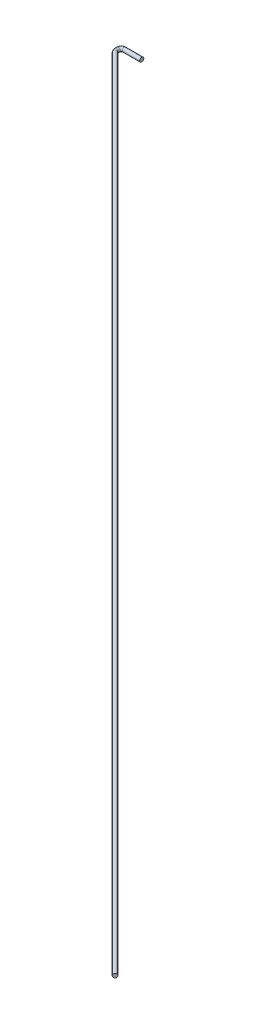
SolidWorks part; units mm, degrees
ref_plane "Front Plane" through (0, 0, 0) normal (0, 0, 1) x (1, 0, 0)
ref_plane "Top Plane" through (0, 0, 0) normal (0, 1, 0) x (1, 0, 0)
ref_plane "Right Plane" through (0, 0, 0) normal (1, 0, 0) x (0, 0, -1)
sketch "Sketch1" plane through (0, 0, 0) normal (0, 1, 0) x (1, 0, 0)
  line L0 (0, 0.6213) -> (0, 1.5)
  line L1 (1.5, 3) -> (10, 3)
  line L2 (0.4393, -0.4393) -> (390.8179, -390.8179)
  arc A0 (0, 1.5) -> (1.5, 3) centre (1.5, 1.5) cw
  arc A1 (0, 0.6213) -> (0.4393, -0.4393) centre (1.5, 0.6213) ccw
  point P7 (0, 3)
  point P10 (0, 0)
  point P11 (0, 0)
  dimension "D5" = 1.5
  dimension "D1" = 135
  dimension "D2" = 10
  dimension "D3" = 3
  dimension "D4" = 552.7
ref_plane "Plane2" through (10, 0, 0) normal (1, 0, 0) x (0, 0, -1)
sketch "Sketch4" plane through (10, 0, 0) normal (1, 0, 0) x (0, 0, -1)
  circle A0 centre (3, 0) radius 1
  dimension "D1" = 2
sweep "Sweep1" add profiles "Sketch4" path "Sketch1"
